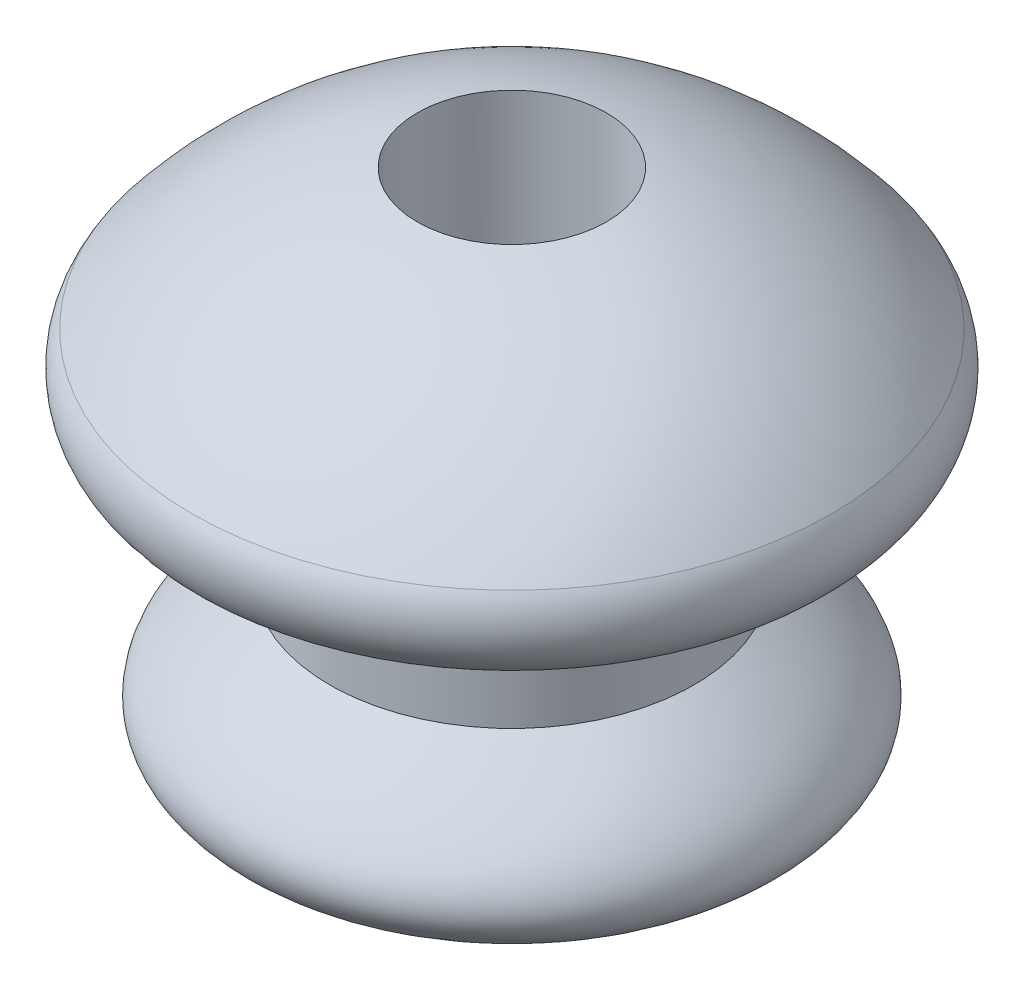
SolidWorks part; units mm, degrees
ref_plane "Front Plane" through (0, 0, 0) normal (0, 0, 1) x (1, 0, 0)
ref_plane "Top Plane" through (0, 0, 0) normal (0, 1, 0) x (1, 0, 0)
ref_plane "Right Plane" through (0, 0, 0) normal (1, 0, 0) x (0, 0, -1)
sketch "Sketch1" plane through (0, 0, 0) normal (0, 0, 1) x (1, 0, 0)
  line L0 (1.9015, -4.1879) -> (1.9015, -2.6879)
  line L1 (1.9015, -2.6879) -> (3.2708, -2.6879)
  line L2 (-0.0247, -0.3102) -> (-0.0247, -6.158)
  line L3 (-0.0247, -6.158) -> (0.3166, -6.158)
  line L4 (-0.0247, 0) -> (-0.0247, -11.6582) construction
  arc A0 (-0.0247, -0.3102) -> (3.3564, -1.8933) centre (0.0503, -4.5519) cw
  arc A1 (3.2708, -1.7903) -> (3.2708, -2.6879) centre (2.8352, -2.2391) cw
  spline S0 degree 3 poles (1.9015, -4.1879) (3.9978, -5.5054) (2.4014, -6.0037) (0.3166, -6.158) knots 0 0 0 0 1 1 1 1
revolve "Revolve1" add sketch "Sketch1" angle 360 about L4
sketch "Sketch2" plane through (0, -6.158, 0) normal (0, -1, 0) x (-1, 0, 0)
  circle A0 centre (0.0247, 0) radius 1
extrude "Cut-Extrude2" cut sketch "Sketch2" against normal through all contours A0
